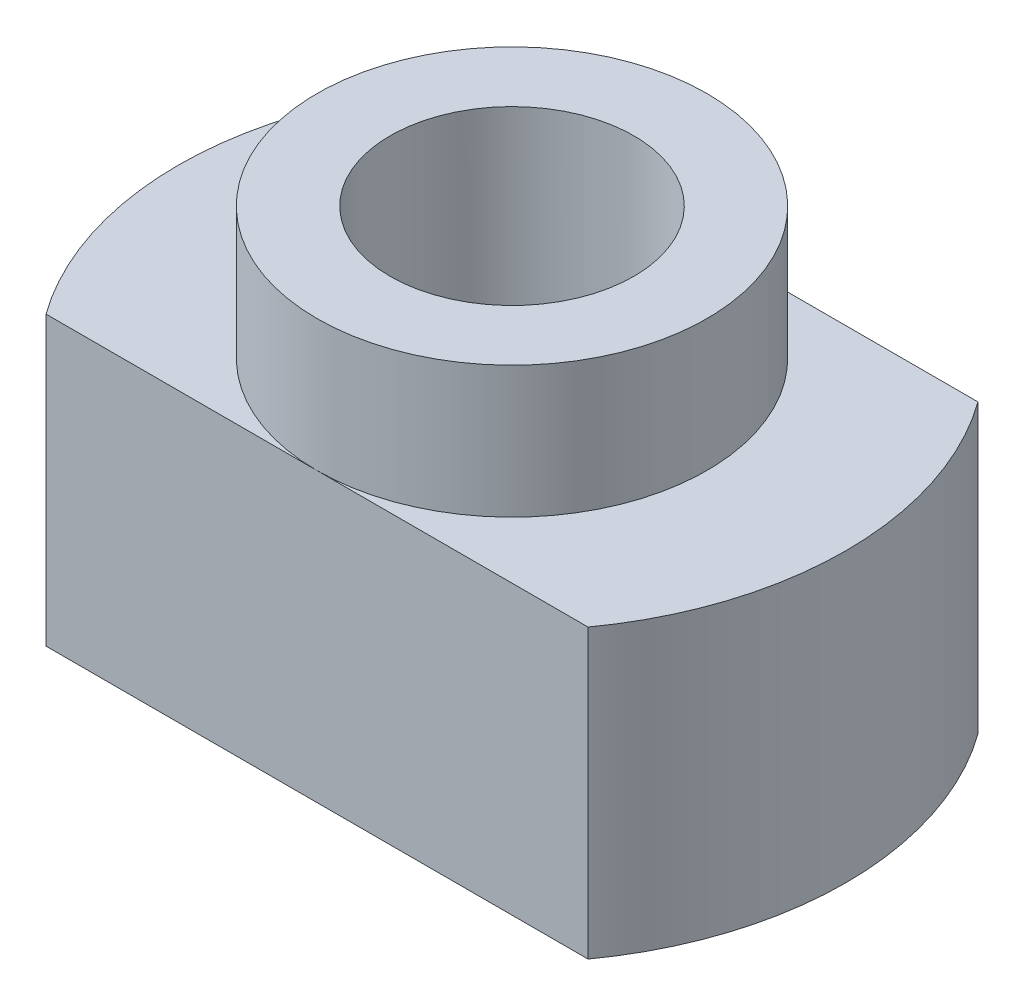
SolidWorks part; units mm, degrees
ref_plane "前视基准面" through (0, 0, 0) normal (0, 0, 1) x (1, 0, 0)
ref_plane "上视基准面" through (0, 0, 0) normal (0, 1, 0) x (1, 0, 0)
ref_plane "右视基准面" through (0, 0, 0) normal (1, 0, 0) x (0, 0, -1)
sketch "草图4" plane through (0, 0, 0) normal (0, 0, 1) x (1, 0, 0)
  line B0 (0, 0) -> (0, 8.6)
  line B1 (6.85, 0) -> (0, 0)
  line B2 (6.85, 5.9) -> (6.85, 0)
  line B3 (6.85, 5.9) -> (4, 5.9)
  line B4 (4, 8.6) -> (4, 5.9)
  line B5 (4, 8.6) -> (0, 8.6)
sketch_block_instance "A$C4A7D1384-1"
sketch_block "A$C4A7D1384"
revolve "旋转2" add sketch "草图4" angle 360 about L0
sketch "草图6" plane through (0, 5.9, 0) normal (0, 1, 0) x (1, 0, 0)
  line L0 (0, 0) -> (-14.6825, 0) construction
  line L1 (-11.2711, 10.4817) -> (8.0717, 10.4817)
  line L2 (-11.2711, 10.4817) -> (-11.2711, 4)
  line L3 (-11.2711, 4) -> (8.0717, 4)
  line L4 (8.0717, 10.4817) -> (8.0717, 4)
  line L5 (8.0717, -10.4817) -> (8.0717, -4)
  line L6 (-11.2711, -4) -> (8.0717, -4)
  line L7 (-11.2711, -10.4817) -> (-11.2711, -4)
  line L8 (-11.2711, -10.4817) -> (8.0717, -10.4817)
  dimension "D1" = 4
extrude "切除-拉伸2" cut sketch "草图6" against normal through all
sketch "草图7" plane through (0, 8.6, 0) normal (0, 1, 0) x (1, 0, 0)
  point P0 (0, 0)
hole_wizard "M6 螺纹孔1" positions "3D草图1" profile "草图8" tap size "M6" standard "Iso"
sketch3d "3D草图1"
  point P0 (0, 8.6, 0)
sketch "草图8" plane through (0, 8.6, 0) normal (1, 0, 0) x (0, 0, 1)
  line L0 (0, 0) -> (0, 29.5022)
  line L1 (0, 29.5022) -> (2.5, 28)
  line L2 (2.5, 28) -> (2.5, 0)
  line L5 (2.5, 0) -> (0, 0)
  line L10 (0, 29.5022) -> (-2.5, 28) construction
  line L11 (0, -6.35) -> (0, 107.95) construction
  dimension "螺纹孔钻头直径" = 5
  dimension "螺纹孔钻头深度" = 28
  dimension "导头角度" = 118
cosmetic thread "孔螺蚊线1" parameters "D1"=8.6, "D2"=6
